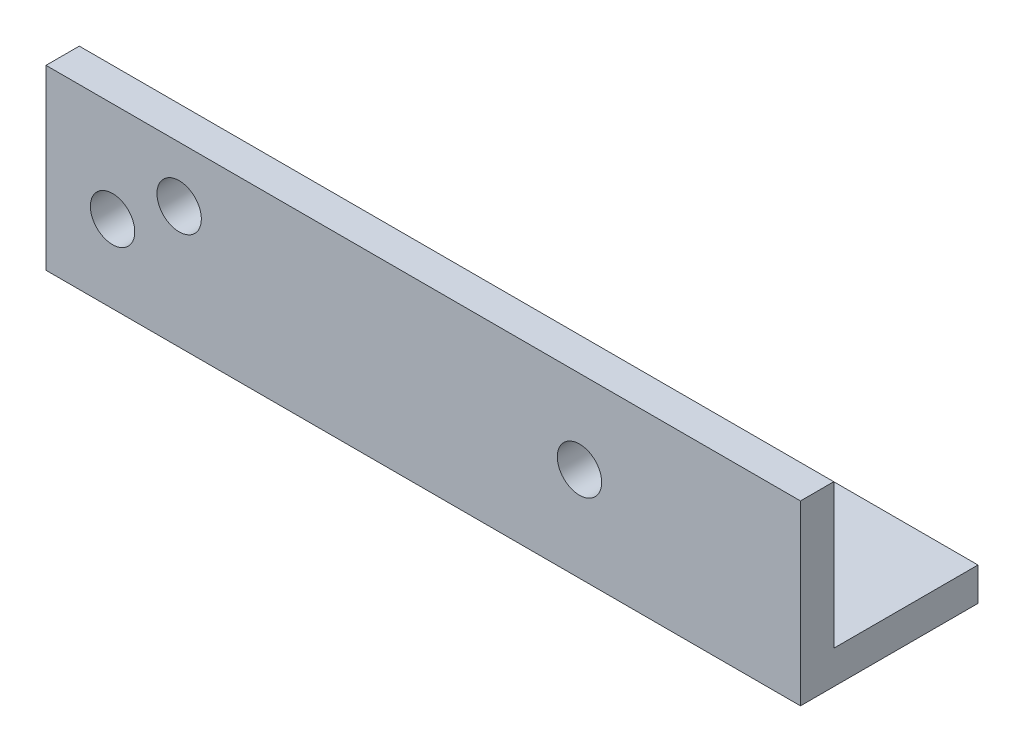
SolidWorks part; units mm, degrees
material "6061 Alloy"
ref_plane "Front Plane" through (0, 0, 0) normal (0, 0, 1) x (1, 0, 0)
ref_plane "Top Plane" through (0, 0, 0) normal (0, 1, 0) x (1, 0, 0)
ref_plane "Right Plane" through (0, 0, 0) normal (1, 0, 0) x (0, 0, -1)
sketch "Sketch1" plane through (0, 0, 0) normal (1, 0, 0) x (0, 0, -1)
  line L0 (0, 0) -> (0, -25.4)
  line L1 (0, -25.4) -> (25.4, -25.4)
  line L2 (25.4, -25.4) -> (25.4, -20.6375)
  line L3 (25.4, -20.6375) -> (4.7625, -20.6375)
  line L4 (4.7625, -20.6375) -> (4.7625, 0)
  line L5 (4.7625, 0) -> (0, 0)
  dimension "D1" = 4.7625
  dimension "D2" = 4.7625
  dimension "D3" = 25.4
  dimension "D4" = 25.4
extrude "Boss-Extrude1" add sketch "Sketch1" along normal blind 107.95
sketch "Sketch3" plane through (0, 0, -4.7625) normal (0, 0, -1) x (-1, 0, 0)
  line L0 (0, -20.6375) -> (0, 0) construction
  line L1 (-107.95, -25.4) -> (0, -25.4) construction
  circle A0 centre (-9.525, -14.2875) radius 3.175
  circle A1 centre (-19.05, -7.9375) radius 3.175
  dimension "D1" = 6.35
  dimension "D2" = 6.35
  dimension "D3" = 9.525
  dimension "D4" = 19.05
  dimension "D5" = 11.1125
  dimension "D6" = 17.4625
extrude "Cut-Extrude1" cut sketch "Sketch3" against normal up to next
sketch "Sketch4" plane through (0, 0, 0) normal (0, 0, 1) x (1, 0, 0)
  circle A0 centre (76.3322, -11.9296) radius 3.175 construction
  circle A1 centre (76.3322, -11.9296) radius 3.175
extrude "Cut-Extrude2" cut sketch "Sketch4" against normal up to next
sketch "Sketch5" plane through (0, -25.4, 0) normal (0, -1, 0) x (1, 0, 0)
  circle A0 centre (69.85, -12.7) radius 3.175 construction
  circle A1 centre (95.25, -12.7) radius 3.175 construction
  circle A2 centre (69.85, -12.7) radius 3.175
  circle A3 centre (95.25, -12.7) radius 3.175
extrude "Cut-Extrude4" cut sketch "Sketch5" against normal up to next
